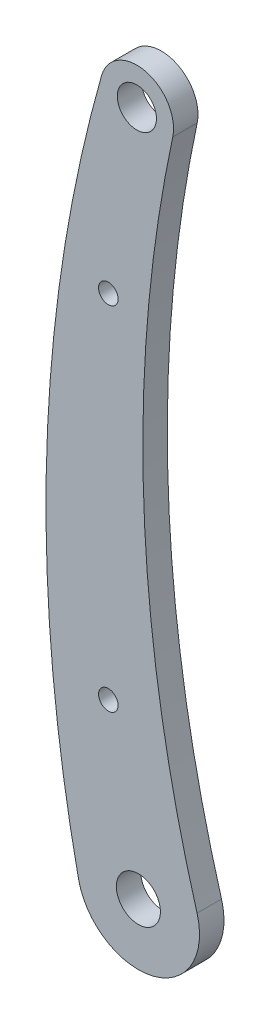
SolidWorks part; units mm, degrees
ref_plane "Piano frontale" through (0, 0, 0) normal (0, 0, 1) x (1, 0, 0)
ref_plane "Piano superiore" through (0, 0, 0) normal (0, 1, 0) x (1, 0, 0)
ref_plane "Piano destro" through (0, 0, 0) normal (1, 0, 0) x (0, 0, -1)
sketch "Schizzo1" plane through (0, 0, 0) normal (0, 0, 1) x (1, 0, 0)
  circle A0 centre (0, 0) radius 4.5
  circle A1 centre (-0.3094, 139.9997) radius 4
  arc A2 (7.024, 138.4277) -> (-7.5254, 142.0442) centre (-0.3094, 139.9997) ccw
  arc A3 (-12.2223, -2.6202) -> (11.9963, 3.5125) centre (0, 0) ccw
  arc A4 (-7.5254, 142.0442) -> (-12.2223, -2.6202) centre (281.1129, 60.2643) ccw
  arc A5 (7.024, 138.4277) -> (11.9963, 3.5125) centre (275.9157, 80.7886) ccw
  dimension "D1" = 8
  dimension "D2" = 9
  dimension "D4" = 15
  dimension "D5" = 25
  dimension "D6" = 600
  dimension "D7" = 550
  dimension "D3" = 140
extrude "Estrusione-Estrusione1" add sketch "Schizzo1" along normal blind 5
sketch "Schizzo2" plane through (0, 0, 5) normal (0, 0, 1) x (1, 0, 0)
  circle A0 centre (-6.1421, 104.1667) radius 2
  circle A1 centre (-6.1421, 32.2137) radius 2
  dimension "D1" = 4
  dimension "D2" = 4
extrude "Taglio-Estrusione1" cut sketch "Schizzo2" against normal blind 25
